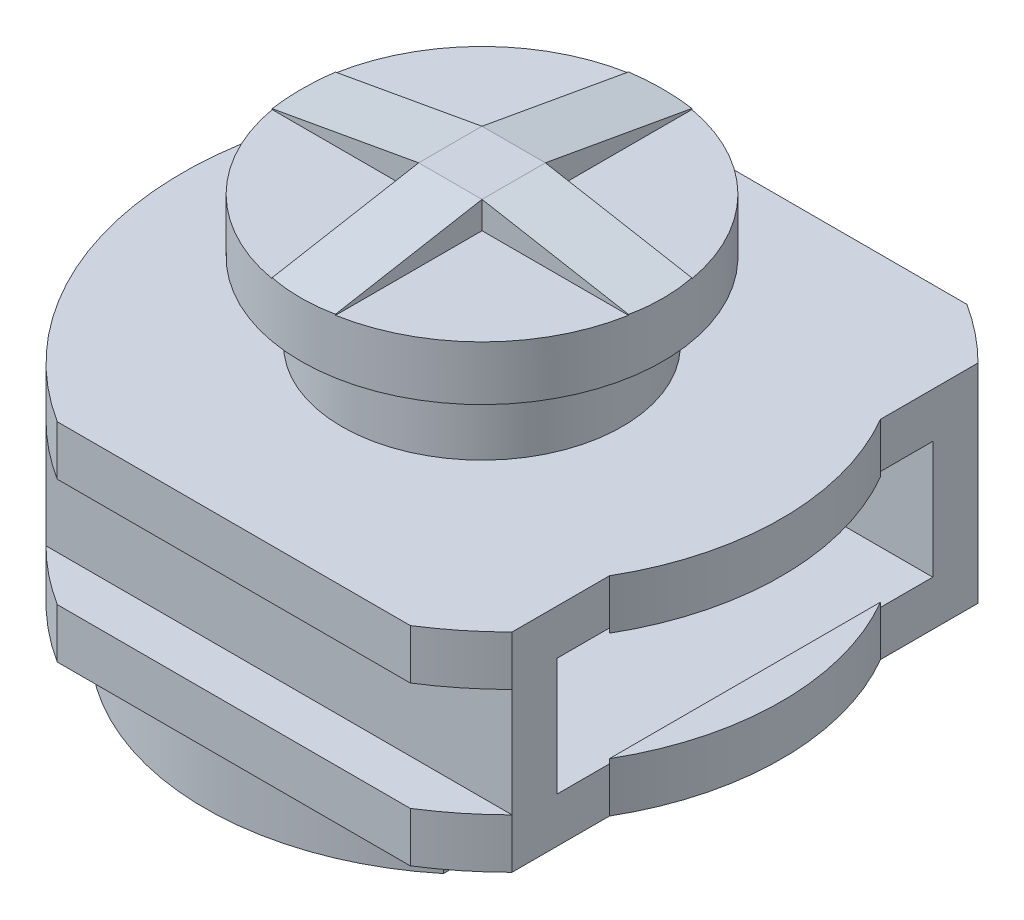
SolidWorks part; units mm, degrees
ref_plane "Front Plane" through (0, 0, 0) normal (0, 0, 1) x (1, 0, 0)
ref_plane "Top Plane" through (0, 0, 0) normal (0, 1, 0) x (1, 0, 0)
ref_plane "Right Plane" through (0, 0, 0) normal (1, 0, 0) x (0, 0, -1)
sketch "Sketch5" plane through (0, 0, 0) normal (0, 1, 0) x (1, 0, 0)
  line L1 (-5.0016, -3.942) -> (5.2984, -3.942)
  line L2 (-5.0016, -3.942) -> (-5.0016, 6.358)
  line L3 (-5.0016, 6.358) -> (5.2984, 6.358)
  line L4 (5.2984, -3.942) -> (5.2984, 6.358)
  dimension "D1" = 10.3
  dimension "D2" = 10.3
extrude "Boss-Extrude2" add sketch "Sketch5" along normal blind 4.6
sketch "Sketch6" plane through (5.2984, 0, 0) normal (1, 0, 0) x (0, 0, -1)
  line L0 (1.208, 4.6) -> (1.208, 0) construction
  line L3 (-3.942, 4.6) -> (6.358, 4.6) construction
  line L4 (-2.942, 1) -> (5.358, 1)
  line L5 (-2.942, 1) -> (-2.942, 3.6)
  line L6 (-2.942, 3.6) -> (5.358, 3.6)
  line L7 (5.358, 1) -> (5.358, 3.6)
  line L8 (-3.942, 4.6) -> (-3.942, 0) construction
  line L9 (-3.942, 0) -> (6.358, 0) construction
  line L10 (6.358, 4.6) -> (6.358, 0) construction
  dimension "D1" = 1
  dimension "D2" = 1
  dimension "D3" = 1
  dimension "D4" = 1
extrude "Cut-Extrude3" cut sketch "Sketch6" against normal blind 9.3
sketch "Sketch7" plane through (0, 4.6, 0) normal (0, 1, 0) x (1, 0, 0)
  line L0 (-5.0016, 1.208) -> (5.2984, 1.208) construction
  line L1 (-3.7532, 7.358) -> (4.05, 7.358)
  line L2 (5.2984, 6.358) -> (-5.0016, 6.358) construction
  line L3 (0.1484, 1010.6244) -> (0.1484, 8.4912) construction
  line L4 (-3.7532, -4.942) -> (4.05, -4.942)
  line L5 (0.1484, 7.358) -> (0.1484, -3.942) construction
  line L7 (5.2984, 6.358) -> (5.2984, 4.2037)
  line L8 (5.2984, -1.7877) -> (5.2984, -3.942)
  line L9 (5.2984, -1.7877) -> (5.2984, -3.942)
  arc A0 (-3.7532, 7.358) -> (-3.7532, -4.942) centre (0.1484, 1.208) ccw
  arc A1 (4.05, -4.942) -> (5.2984, -3.942) centre (0.1484, 1.208) ccw
  arc A2 (5.2984, -1.7877) -> (5.2984, 4.2037) centre (0.1484, 1.208) ccw
  arc A3 (5.2984, 6.358) -> (4.05, 7.358) centre (0.1484, 1.208) ccw
  dimension "D1" = 1
extrude "Boss-Extrude4" add sketch "Sketch7" against normal blind 1.1
ref_plane "Plane1" through (0, 2.3, 0) normal (0, 1, 0) x (1, 0, 0)
mirror "Mirror1" about plane through (0, 2.3, 0) normal (0, 1, 0) of "Boss-Extrude4", "Cut-Extrude3"
sketch "Sketch8" plane through (0, 1.1, 0) normal (0, 1, 0) x (1, 0, 0)
  line L0 (-6.3348, 4.5266) -> (-6.3348, -2.1106)
  line L1 (-5.0016, 6.358) -> (-5.0016, -3.942)
  arc A0 (-5.0016, 6.358) -> (-5.0016, -3.942) centre (0.1484, 1.208) ccw construction
  arc A1 (-6.3348, -2.1106) -> (-5.0016, -3.942) centre (0.1484, 1.208) ccw
  arc A2 (-5.0016, 6.358) -> (-6.3348, 4.5266) centre (0.1484, 1.208) ccw
  point P5 (-7.1348, 1.208)
  dimension "D1" = 0.8
extrude "Boss-Extrude5" add sketch "Sketch8" along normal up to next
sketch "Sketch9" plane through (0, 0, 0) normal (0, -1, 0) x (1, 0, 0)
  line L0 (-7.1348, -1.208) -> (6.1063, -1.208) construction
  line L1 (-0.5143, -1.208) -> (-0.5143, 4.942) construction
sketch "Sketch10" plane through (0, 0, 0) normal (0, -1, 0) x (1, 0, 0)
  line L0 (-200007.1348, -1.208) -> (200006.1063, -1.208) construction
  circle A0 centre (-0.5143, -1.208) radius 2
  dimension "D1" = 4
extrude "Cut-Extrude4" cut sketch "Sketch10" against normal through all
sketch "Sketch11" plane through (0, 4.6, 0) normal (0, 1, 0) x (1, 0, 0)
  line L0 (-200007.1348, 1.208) -> (200006.1063, 1.208) construction
  circle A0 centre (-0.5143, 1.208) radius 3.1
  circle A1 centre (-0.5143, 1.208) radius 2 construction
  circle A2 centre (-0.5143, 1.208) radius 2
  dimension "D1" = 1.1
extrude "Boss-Extrude6" add sketch "Sketch11" along normal blind 1.7
sketch "Sketch12" plane through (0, 6.3, 0) normal (0, 1, 0) x (1, 0, 0)
  line L0 (-200007.1348, 1.208) -> (200006.1063, 1.208) construction
  circle A0 centre (-0.5143, 1.208) radius 4
  dimension "D1" = 8
extrude "Boss-Extrude7" add sketch "Sketch12" along normal blind 1.2
sketch "Sketch13" plane through (0, 7.5, 0) normal (0, 1, 0) x (1, 0, 0)
  line L0 (-200007.1348, 1.208) -> (200006.1063, 1.208) construction
  line L1 (-1.2143, 5.1463) -> (-1.2143, 1.908)
  line L2 (0.1857, 5.1463) -> (0.1857, 1.908)
  line L3 (-4.4526, 1.908) -> (-1.2143, 1.908)
  line L4 (-4.4526, 0.508) -> (-1.2143, 0.508)
  line L6 (-0.5143, 200001.208) -> (-0.5143, -200004.942) construction
  line L7 (0.1857, 0.508) -> (0.1857, -2.7302)
  line L8 (-1.2143, 0.508) -> (-1.2143, -2.7302)
  line L9 (0.1857, 1.908) -> (3.424, 1.908)
  line L10 (0.1857, 0.508) -> (3.424, 0.508)
  arc A0 (-4.4526, 1.908) -> (-4.4526, 0.508) centre (-0.5143, 1.208) ccw
  arc A1 (0.1857, 5.1463) -> (-1.2143, 5.1463) centre (-0.5143, 1.208) ccw
  arc A2 (3.424, 0.508) -> (3.424, 1.908) centre (-0.5143, 1.208) ccw
  arc A3 (-1.2143, -2.7302) -> (0.1857, -2.7302) centre (-0.5143, 1.208) ccw
  dimension "D3" = 8
  dimension "D1" = 1.4
  dimension "D2" = 0.7
  dimension "D4" = 1.4
  dimension "D5" = 0.7
extrude "Boss-Extrude8" add sketch "Sketch13" along normal blind 0.6
ref_plane "Plane2" through (0, 0, -1.208) normal (0, 0, -1) x (-1, 0, 0)
sketch "Sketch14" plane through (0.1857, 0, 0) normal (1, 0, 0) x (0, 0, -1)
  line L1 (-2.8486, 7.5) -> (0.508, 8.1)
  line L7 (-2.8486, 7.5) -> (-2.8486, 8.1)
  line L8 (-2.8486, 8.1) -> (0.508, 8.1)
  line L9 (1.208, -7.3202) -> (1.208, 7.3202) construction
  line L10 (5.2647, 7.5) -> (1.908, 8.1)
  line L11 (5.2647, 7.5) -> (5.2647, 8.1)
  line L12 (5.2647, 8.1) -> (1.908, 8.1)
extrude "Cut-Extrude7" cut sketch "Sketch14" against normal through all
sketch "Sketch15" plane through (0, 0, -0.508) normal (0, 0, 1) x (1, 0, 0)
  line L0 (-0.5143, 8.1) -> (-0.5143, 6.6066) construction
  line L2 (3.5215, 8.1) -> (3.5215, 7.5)
  line L3 (-4.5501, 7.5) -> (-1.2143, 8.1)
  line L4 (-1.2143, 8.1) -> (-4.5501, 8.1)
  line L5 (-4.5501, 8.1) -> (-4.5501, 7.5)
  line L6 (0.1857, 8.1) -> (3.5215, 8.1)
  line L7 (3.5215, 7.5) -> (0.1857, 8.1)
extrude "Cut-Extrude8" cut sketch "Sketch15" against normal through all
sketch "Sketch16" plane through (0, 0, 0) normal (0, -1, 0) x (1, 0, 0)
  circle A0 centre (-0.5143, -1.208) radius 6.1184
  circle A1 centre (-0.5143, -1.208) radius 4.9184
  dimension "D1" = 1.2
extrude "Boss-Extrude9" add sketch "Sketch16" along normal blind 1.2
sketch "Sketch17" plane through (0, -1.2, 0) normal (0, -1, 0) x (1, 0, 0)
  line L0 (3.3646, 1.816) -> (3.3646, -4.2321)
  line L1 (3.3646, 1.816) -> (3.3646, 3.5237)
  line L2 (3.3646, -4.2321) -> (3.4157, -5.8974)
  circle A0 centre (-0.5143, -1.208) radius 4.9184 construction
  circle A1 centre (-0.5143, -1.208) radius 6.1184 construction
  circle A2 centre (-0.5143, -1.208) radius 6.1184 construction
  arc A3 (3.3646, 3.5237) -> (3.4157, -5.8974) centre (-0.5143, -1.208) cw
extrude "Cut-Extrude9" cut sketch "Sketch17" against normal blind 1.2
